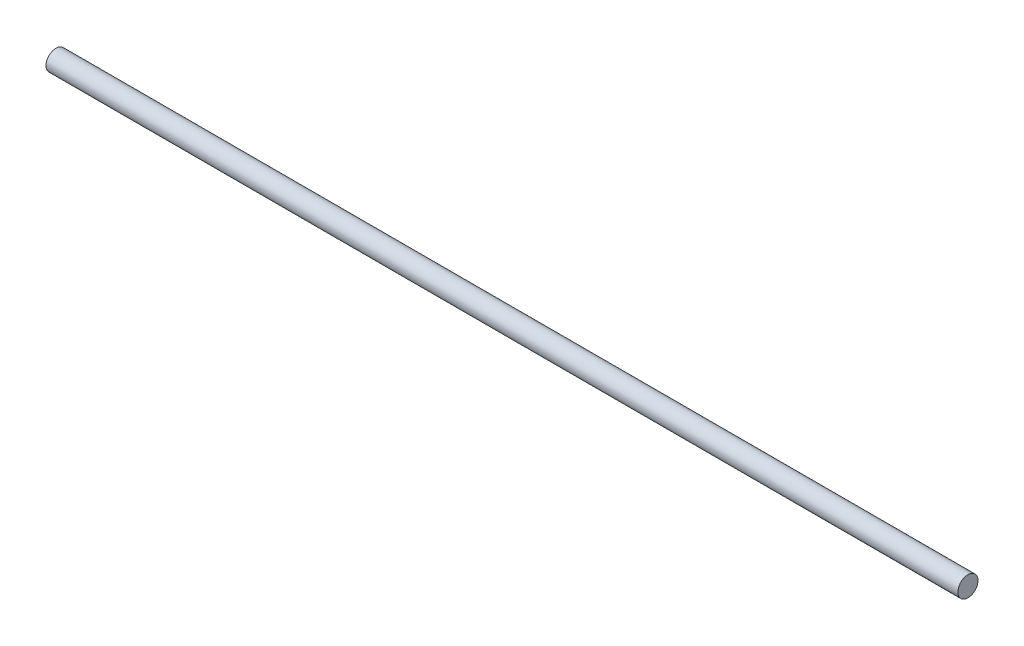
SolidWorks part; units mm, degrees
ref_plane "Front Plane" through (0, 0, 0) normal (0, 0, 1) x (1, 0, 0)
ref_plane "Top Plane" through (0, 0, 0) normal (0, 1, 0) x (1, 0, 0)
ref_plane "Right Plane" through (0, 0, 0) normal (1, 0, 0) x (0, 0, -1)
sketch "Sketch1" plane through (0, 0, 0) normal (1, 0, 0) x (0, 0, -1)
  circle A0 centre (0, 0) radius 7.5
  dimension "D1" = 15
extrude "Boss-Extrude1" add sketch "Sketch1" along normal blind 680
